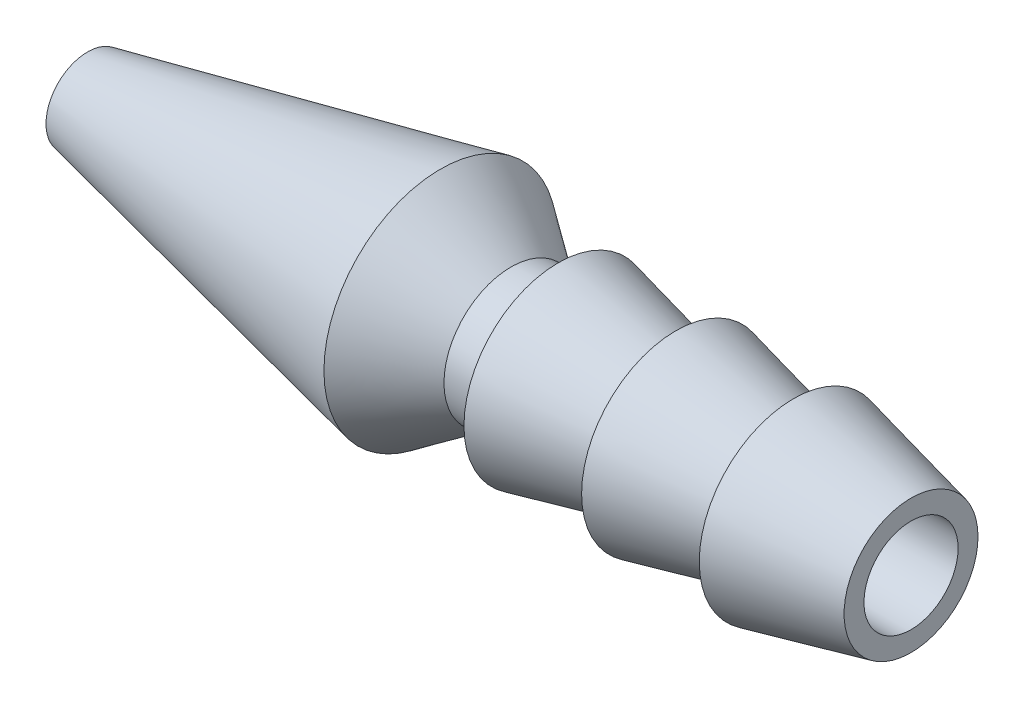
SolidWorks part; units mm, degrees
ref_plane "Front Plane" through (0, 0, 0) normal (0, 0, 1) x (1, 0, 0)
ref_plane "Top Plane" through (0, 0, 0) normal (0, 1, 0) x (1, 0, 0)
ref_plane "Right Plane" through (0, 0, 0) normal (1, 0, 0) x (0, 0, -1)
sketch "Sketch1" plane through (0, 0, 0) normal (1, 0, 0) x (0, 0, -1)
  circle A0 centre (0, 0) radius 4
extrude "Boss-Extrude1" add sketch "Sketch1" along normal blind 5 draft 13
sketch "Sketch2" plane through (5, 0, 0) normal (1, 0, 0) x (0, 0, -1)
  circle A0 centre (0, 0) radius 4
extrude "Boss-Extrude2" add sketch "Sketch2" along normal blind 5 draft 13
sketch "Sketch3" plane through (10, 0, 0) normal (1, 0, 0) x (0, 0, -1)
  circle A0 centre (0, 0) radius 4
extrude "Boss-Extrude3" add sketch "Sketch3" along normal blind 5 draft 13
sketch "Sketch4" plane through (0, 0, 0) normal (-1, 0, 0) x (0, 0, 1)
  circle A0 centre (0, 0) radius 2.85
extrude "Boss-Extrude4" add sketch "Sketch4" along normal blind 2
sketch "Sketch5" plane through (-2, 0, 0) normal (-1, 0, 0) x (0, 0, 1)
  circle A0 centre (0, 0) radius 2.85
extrude "Boss-Extrude5" add sketch "Sketch5" along normal blind 3 draft 35 draft outward yes
sketch "Sketch6" plane through (-5, 0, 0) normal (-1, 0, 0) x (0, 0, 1)
  circle A0 centre (0, 0) radius 4.9506
extrude "Boss-Extrude6" add sketch "Sketch6" along normal blind 15 draft 12
sketch "Sketch9" plane through (15, 0, 0) normal (1, 0, 0) x (0, 0, -1)
  circle A0 centre (0, 0) radius 2
extrude "Cut-Extrude1" cut sketch "Sketch9" against normal blind 20
sketch "Sketch12" plane through (-20, 0, 0) normal (-1, 0, 0) x (0, 0, 1)
  line L1 (-1.24, 0.2) -> (1.24, 0.2)
  line L2 (-1.24, 0.2) -> (-1.24, -0.2)
  line L3 (-1.24, -0.2) -> (1.24, -0.2)
  line L4 (1.24, 0.2) -> (1.24, -0.2)
  line L5 (-1.24, 0.2) -> (1.24, -0.2) construction
  line L6 (-1.24, -0.2) -> (1.24, 0.2) construction
  point P0 (0, 0)
  dimension "D1" = 2.4799
  dimension "D2" = 0.4
extrude "Cut-Extrude10" cut sketch "Sketch12" against normal blind 10
sketch "Sketch14" plane through (-5, 0, 0) normal (1, 0, 0) x (0, 0, -1)
  circle A0 centre (0, 0) radius 2
extrude "Cut-Extrude11" cut sketch "Sketch14" against normal blind 10 draft 11.2
